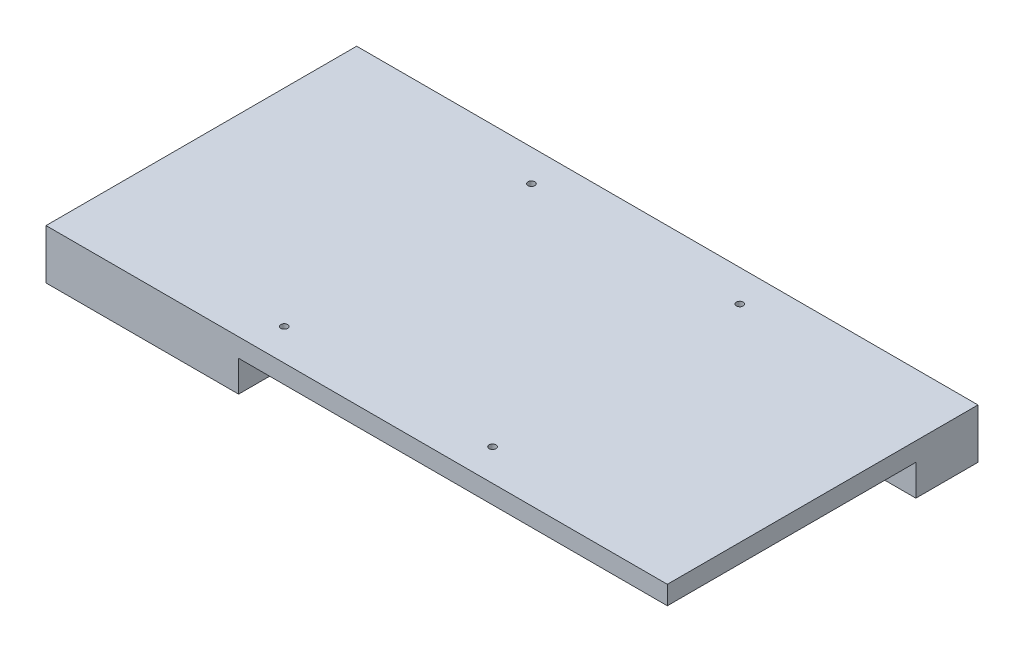
SolidWorks part; units mm, degrees
material "PVC 0.007 Plasticized"
ref_plane "Front Plane" through (0, 0, 0) normal (0, 0, 1) x (1, 0, 0)
ref_plane "Top Plane" through (0, 0, 0) normal (0, 1, 0) x (1, 0, 0)
ref_plane "Right Plane" through (0, 0, 0) normal (1, 0, 0) x (0, 0, -1)
sketch "Sketch2" plane through (0, 0, 0) normal (0, 1, 0) x (1, 0, 0)
  line L1 (0, 0) -> (200, 0)
  line L2 (0, 0) -> (0, -100)
  line L3 (0, -100) -> (200, -100)
  line L4 (200, 0) -> (200, -100)
  dimension "D1" = 200
  dimension "D2" = 100
extrude "Boss-Extrude1" add sketch "Sketch2" along normal blind 6
sketch "Sketch3" plane through (0, 6, 0) normal (0, 1, 0) x (1, 0, 0)
  line L0 (0, -89.79) -> (200, -89.79) construction
  line L1 (0, 0) -> (0, -100) construction
  line L2 (200, -100) -> (200, 0) construction
  line L3 (200, -10.21) -> (0, -10.21) construction
  line L4 (66.465, -10.21) -> (133.535, -10.21) construction
  line L6 (200, 0) -> (0, 0) construction
  circle A0 centre (66.465, -10.21) radius 1.1
  circle A1 centre (133.535, -10.21) radius 1.1
  point P17 (100, 0)
  point P18 (100, -10.21)
  dimension "D3" = 2.2
  dimension "D1" = 10.21
  dimension "D2" = 10.21
  dimension "D4" = 67.07
extrude "Cut-Extrude1" cut sketch "Sketch3" against normal up to surface (6 mm away) up to face at (100, 0, 50)
ref_plane "Plane1" through (0, 0, 50) normal (0, 0, 1) x (1, 0, 0)
mirror "Mirror1" about plane through (0, 0, 50) normal (0, 0, 1) of "Cut-Extrude1"
sketch "Sketch4" plane through (0, 0, 0) normal (0, -1, 0) x (1, 0, 0)
  line L0 (200, 100) -> (200, 0) construction
  line L1 (0, 100) -> (62, 100)
  line L2 (0, 100) -> (0, 80)
  line L3 (0, 80) -> (62, 80)
  line L4 (62, 100) -> (62, 80)
  line L5 (200, 20) -> (138, 20)
  line L6 (200, 20) -> (200, 0)
  line L7 (200, 0) -> (138, 0)
  line L8 (138, 20) -> (138, 0)
  line L9 (200, 0) -> (0, 0) construction
  dimension "D1" = 62
  dimension "D2" = 20
extrude "Boss-Extrude2" add sketch "Sketch4" along normal blind 10
